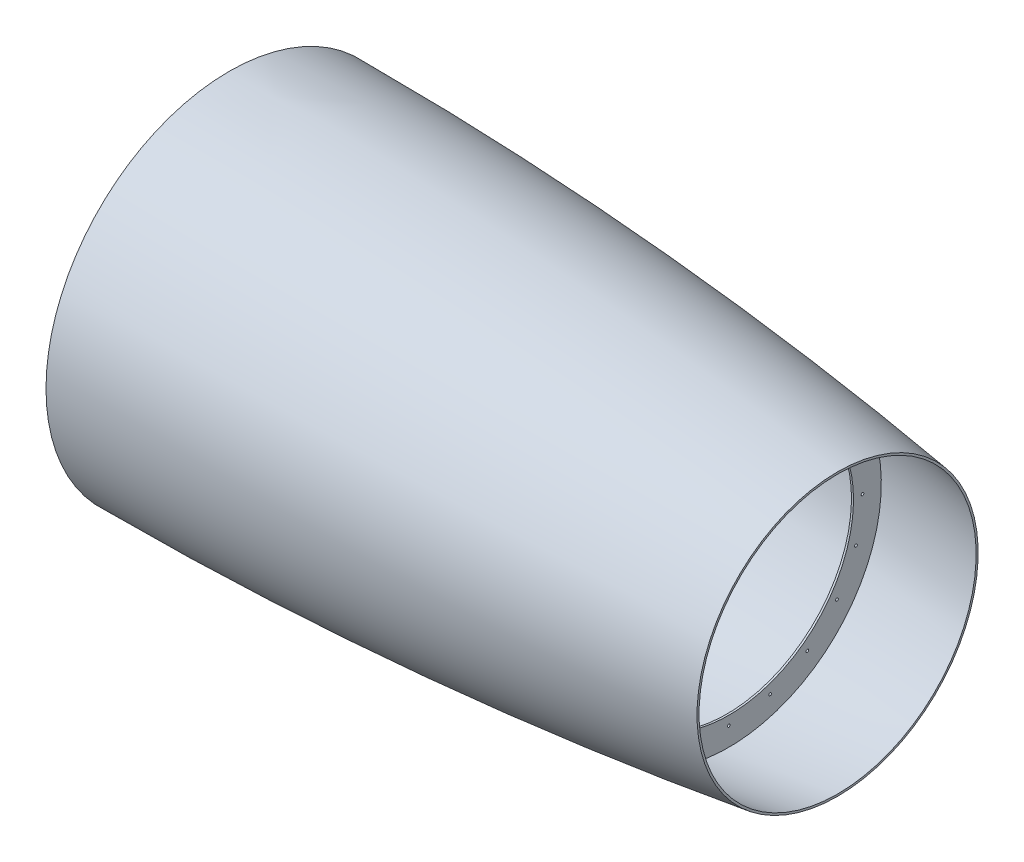
SolidWorks part; units mm, degrees
ref_plane "Front Plane" through (0, 0, 0) normal (0, 0, 1) x (1, 0, 0)
ref_plane "Top Plane" through (0, 0, 0) normal (0, 1, 0) x (1, 0, 0)
ref_plane "Right Plane" through (0, 0, 0) normal (1, 0, 0) x (0, 0, -1)
sketch "Sketch1" plane through (0, 0, 0) normal (0, 0, 1) x (1, 0, 0)
  line L0 (455, 0) -> (-455, 0) construction
  line L1 (-455, 274) -> (-454.9991, 271)
  line L2 (455, 210.25) -> (455, 207.2203)
  line L3 (292.3009, 228.0959) -> (292.3009, 186.5)
  line L4 (292.3009, 186.5) -> (289.3009, 186.5)
  line L5 (289.3009, 186.5) -> (289.3009, 228.4417)
  line L6 (-454.9991, 271) -> (-454.9991, 244.75)
  line L7 (-454.9991, 244.75) -> (-451.9991, 244.75)
  line L8 (-451.9991, 244.75) -> (-451.9991, 271.0002)
  line L9 (-317.6991, 269.5887) -> (-317.6991, 225)
  line L10 (-317.6991, 225) -> (-314.6991, 225)
  line L11 (-314.6991, 225) -> (-314.6991, 269.5255)
  arc A0 (455, 210.25) -> (-455, 274) centre (-453.1241, -6225.9997) ccw
  arc A1 (455, 207.2203) -> (292.3009, 228.0959) centre (-453.1241, -6225.9997) ccw
  arc A2 (454.5809, 207.2794) -> (-454.9991, 271) centre (-453.1241, -6225.9997) ccw construction
  arc A3 (-317.6991, 269.5887) -> (-451.9991, 271.0002) centre (-453.1241, -6225.9997) ccw
  arc A4 (289.3009, 228.4417) -> (-314.6991, 269.5255) centre (-453.1241, -6225.9997) ccw
  point P4 (0, 0)
  dimension "D1" = 910
  dimension "D2" = 6500
  dimension "D3" = 210.25
  dimension "D4" = 274
  dimension "D6" = 3
  dimension "D7" = 244.75
  dimension "D8" = 225
  dimension "D9" = 3
  dimension "D10" = 134.3
  dimension "D11" = 3
  dimension "D12" = 186.5
  dimension "D13" = 604
  dimension "D5" = 3
revolve "Revolve1" add sketch "Sketch1" angle 360 about L0
sketch "Sketch2" plane through (-454.9991, 0, 0) normal (-1, 0, 0) x (0, 0, 1)
  line L0 (0, 0) -> (40, 256.9047) construction
  circle A0 centre (40, 256.9047) radius 4
  dimension "D2" = 8
  dimension "D1" = 40
  dimension "D3" = 260
extrude "Cut-Extrude1" cut sketch "Sketch2" against normal blind 10
sketch "Sketch3" plane through (292.3009, 0, 0) normal (1, 0, 0) x (0, 0, -1)
  circle A0 centre (0, 200) radius 2
  dimension "D2" = 4
  dimension "D1" = 200
extrude "Cut-Extrude2" cut sketch "Sketch3" against normal blind 10
pattern_circular "CirPattern1" count 20 over 360 about axis through (0, 0, 0) along (1, 0, 0) of "Cut-Extrude2", "Cut-Extrude1"
